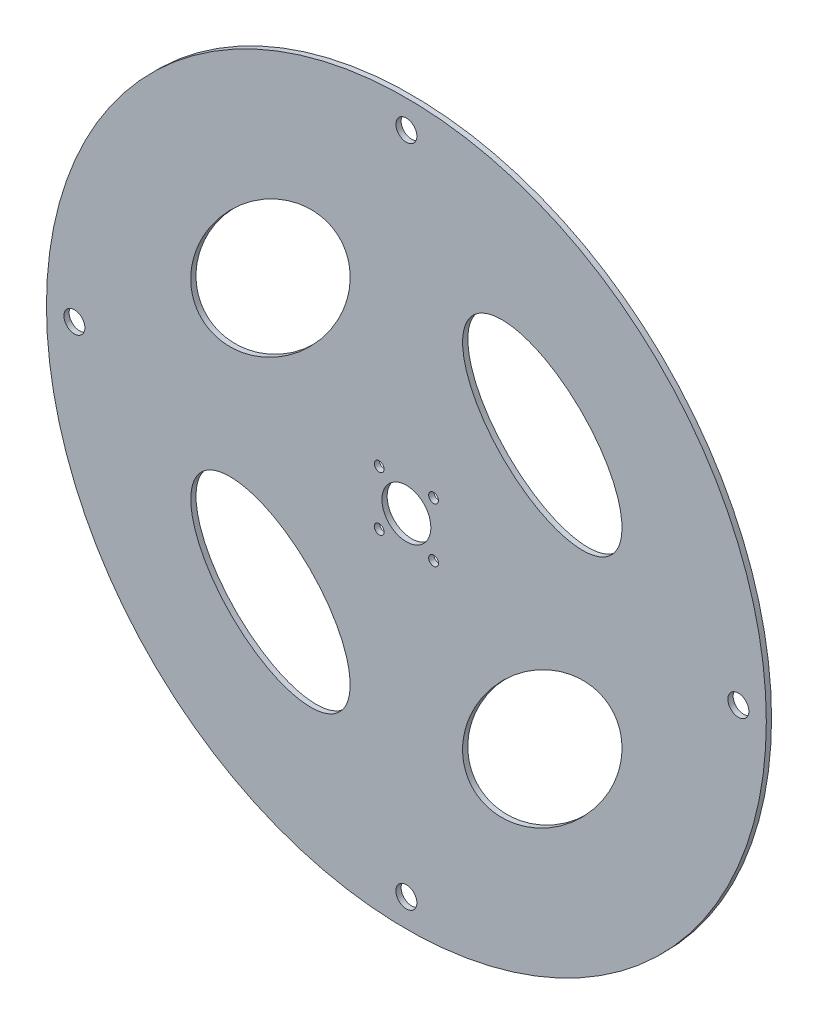
SolidWorks part; units mm, degrees
ref_plane "Front Plane" through (0, 0, 0) normal (0, 0, 1) x (1, 0, 0)
ref_plane "Top Plane" through (0, 0, 0) normal (0, 1, 0) x (1, 0, 0)
ref_plane "Right Plane" through (0, 0, 0) normal (1, 0, 0) x (0, 0, -1)
sketch "Sketch1" plane through (0, 0, 0) normal (0, 0, 1) x (1, 0, 0)
  circle A0 centre (0, 0) radius 103
  dimension "D1" = 206
extrude "Base Disc" add sketch "Sketch1" along normal blind 1.5
sketch "Sketch2" plane through (0, 0, 0) normal (0, 0, -1) x (-1, 0, 0)
  circle A0 centre (0, 0) radius 7.5
sketch "Sketch3" plane through (0, 0, 0) normal (0, 0, -1) x (-1, 0, 0)
  circle A0 centre (95, 0) radius 3
  dimension "D1" = 6
  dimension "D2" = 95
extrude "Cut-Extrude1" cut sketch "Sketch3" against normal through all
sketch "Sketch4" plane through (0, 0, 0) normal (0, 0, -1) x (-1, 0, 0)
  line L0 (0, 0) -> (38.8909, 38.8909) construction
  ellipse E0 centre (38.8909, 38.8909) end of major axis (19.0919, 58.6899) minor radius 16
extrude "Cut-Extrude2" cut sketch "Sketch4" against normal through all
extrude "Cut-Extrude3" cut sketch "Sketch2" against normal through all
pattern_circular "CirPattern3" count 4 over 360 about axis through (0, 0, 0) along (0, 0, 1) of "Cut-Extrude1"
pattern_circular "CirPattern4" count 4 over 360 about axis through (0, 0, 0) along (0, 0, -1) of "Cut-Extrude2"
sketch "Sketch5" plane through (0, 0, 0) normal (0, 0, 1) x (1, 0, 0)
  line L0 (-15.8162, -15.8162) -> (-7.7782, -7.7782) construction
  line L1 (707.1068, -707.1068) -> (-6.7882, 6.7882) construction
  line L2 (-7.7782, 7.7782) -> (-720.1946, 720.1946) construction
  line L3 (-6.7882, -6.7882) -> (7.5537, 7.5537) construction
  circle A1 centre (-7.7782, -7.7782) radius 1.4
  circle A2 centre (-7.7782, 7.7782) radius 1.4
  circle A3 centre (7.7782, 7.7782) radius 1.4
  circle A4 centre (7.7782, -7.7782) radius 1.4
  point P18 (0, 0)
  dimension "D1" = 4
extrude "Cut-Extrude4" cut sketch "Sketch5" along normal through all
sketch "Sketch6" plane through (0, 0, 0) normal (0, 0, 1) x (1, 0, 0)
  circle A0 centre (0, 0) radius 7.51
  circle A1 centre (0, 0) radius 7
extrude "Centre_Bore_Correction_D14" add sketch "Sketch6" along normal blind 1.5
